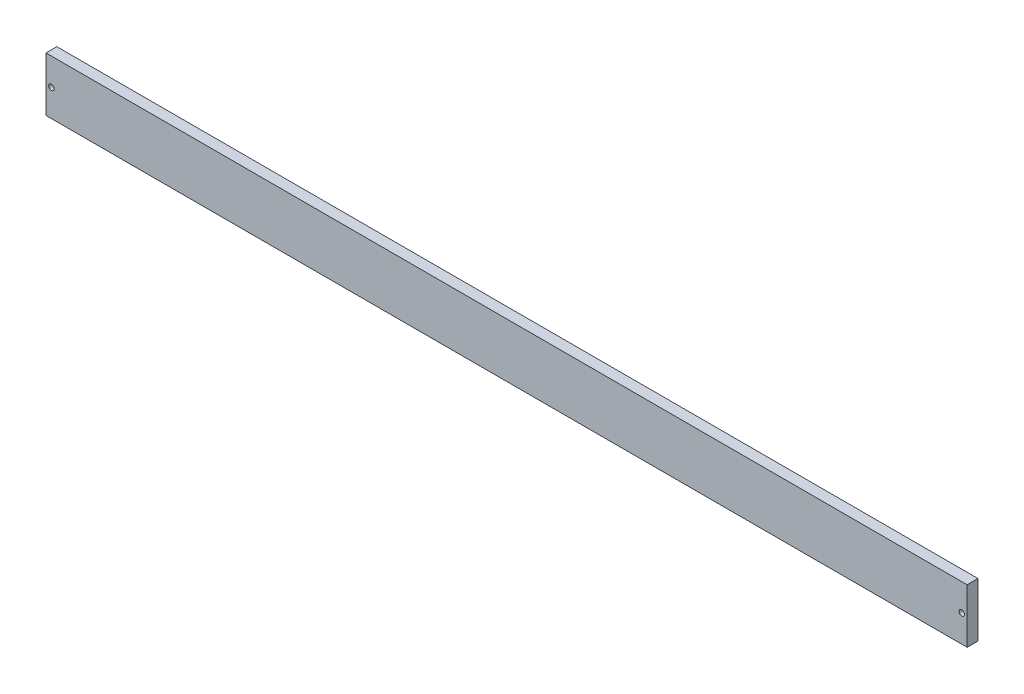
SolidWorks part; units mm, degrees
ref_plane "Alzado" through (0, 0, 0) normal (0, 0, 1) x (1, 0, 0)
ref_plane "Planta" through (0, 0, 0) normal (0, 1, 0) x (1, 0, 0)
ref_plane "Vista lateral" through (0, 0, 0) normal (1, 0, 0) x (0, 0, -1)
sketch "Croquis1" plane through (0, 0, 0) normal (0, 0, 1) x (1, 0, 0)
  line L1 (-425, -25) -> (425, -25)
  line L2 (-425, -25) -> (-425, 25)
  line L3 (-425, 25) -> (425, 25)
  line L4 (425, -25) -> (425, 25)
  line L5 (-425, -25) -> (425, 25) construction
  line L6 (-425, 25) -> (425, -25) construction
  point P0 (0, 0)
  dimension "D1" = 850
  dimension "D2" = 50
extrude "Saliente-Extruir1" add sketch "Croquis1" along normal mid plane 10
sketch "Croquis2" plane through (0, -25, 0) normal (0, -1, 0) x (1, 0, 0)
  line L0 (425, 0) -> (-425, 0) construction
  line L1 (425, 5) -> (425, -5) construction
  line L2 (-425, 5) -> (-425, -5) construction
  circle A0 centre (-375, 0) radius 2.5
  circle A1 centre (-275, 0) radius 2.5
  circle A2 centre (-175, 0) radius 2.5
  circle A3 centre (-75, 0) radius 2.5
  circle A4 centre (25, 0) radius 2.5
  circle A5 centre (125, 0) radius 2.5
  circle A6 centre (225, 0) radius 2.5
  circle A7 centre (325, 0) radius 2.5
  dimension "D1" = 5
  dimension "D2" = 50
  dimension "D3" = 8
extrude "Cortar-Extruir1" cut sketch "Croquis2" against normal blind 5
sketch "Croquis4" plane through (0, 0, -5) normal (0, 0, -1) x (-1, 0, 0)
  line L0 (0, 254.0031) -> (0, -216.8081) construction
  line L1 (-420, 201.8221) -> (-420, -186.1048) construction
  line L2 (-425, -25) -> (-425, 25) construction
  circle A0 centre (-420, 0) radius 2.5
  circle A1 centre (420, 0) radius 2.5
  dimension "D2" = 5
  dimension "D1" = 5
extrude "Cortar-Extruir3" cut sketch "Croquis4" against normal blind 5 from offset 5
